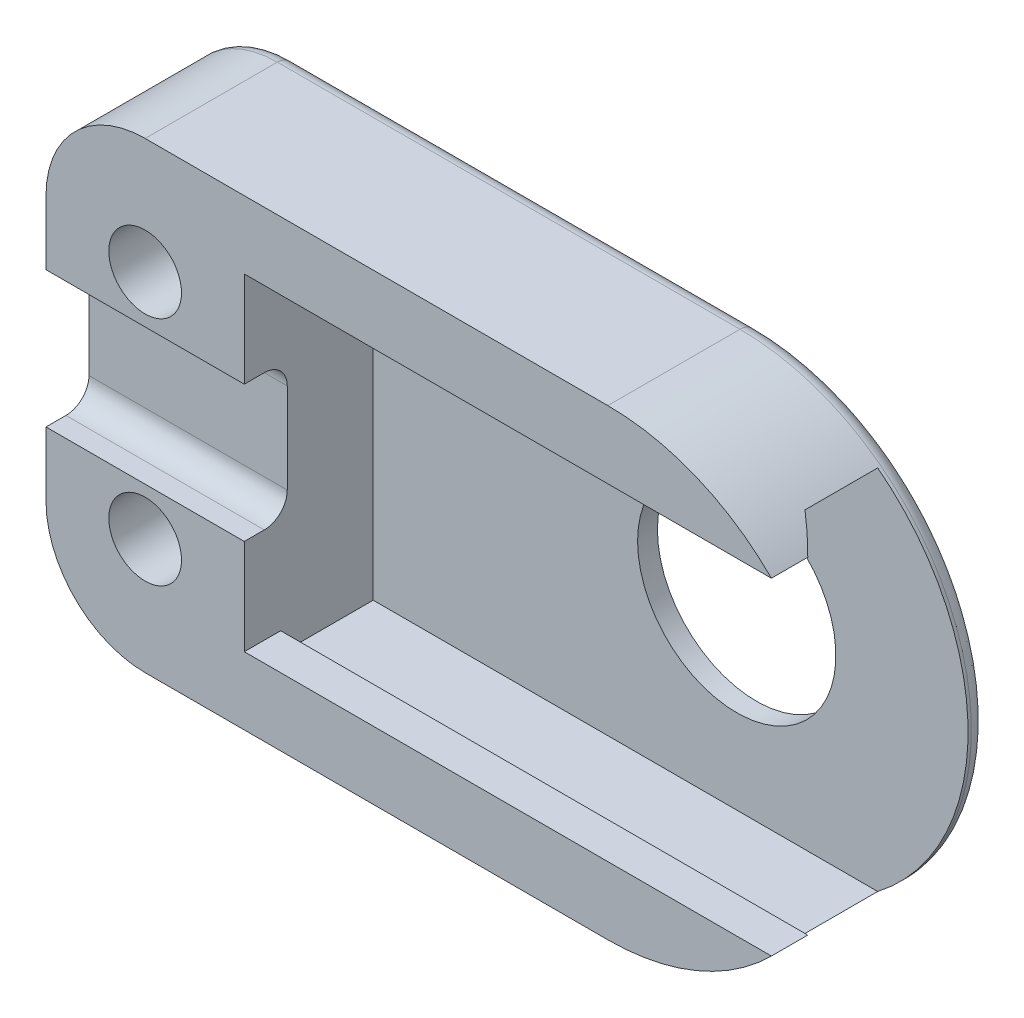
SolidWorks part; units mm, degrees
ref_plane "Front Plane" through (0, 0, 0) normal (0, 0, 1) x (1, 0, 0)
ref_plane "Top Plane" through (0, 0, 0) normal (0, 1, 0) x (1, 0, 0)
ref_plane "Right Plane" through (0, 0, 0) normal (1, 0, 0) x (0, 0, -1)
sketch "Sketch1" plane through (0, 0, 0) normal (0, 0, 1) x (1, 0, 0)
  line L0 (-1.7511, 0) -> (-50001.7511, 0) construction
  line L2 (-17, 7) -> (0, 7)
  line L3 (-17, 7) -> (-17, -7)
  line L4 (-17, -7) -> (0, -7)
  arc A1 (0, 7) -> (0, -7) centre (0, 0) cw
  circle A2 centre (-14, 3.5) radius 1.1
  circle A3 centre (-14, -3.5) radius 1.1
  dimension "D1" = 2.2
  dimension "D2" = 14
  dimension "D3" = 3
  dimension "D4" = 7
  dimension "D5" = 7
extrude "Boss-Extrude1" add sketch "Sketch1" along normal blind 4.5
sketch "Sketch2" plane through (0, 0, 0) normal (0, 0, -1) x (-1, 0, 0)
  circle A0 centre (0, 0) radius 3
  dimension "D1" = 6
extrude "Cut-Extrude2" cut sketch "Sketch2" against normal blind 10
sketch "Sketch7" plane through (-17, 0, 0) normal (-1, 0, 0) x (0, 0, 1)
  line L1 (0.6, 5.55) -> (0.6, -5.55)
  line L2 (0.6, 5.55) -> (2.8, 5.55)
  line L3 (2.8, 5.55) -> (3.4, 4.95)
  line L4 (3.4, 4.95) -> (4.5, 4.95)
  line L5 (4.5, 7) -> (4.5, -7) construction
  line L6 (0, 0) -> (8.4762, 0) construction
  line L7 (0.6, 0) -> (4.5, 0)
  line L8 (4.5, -4.95) -> (4.5, 4.95)
  line L9 (3.4, -4.95) -> (4.5, -4.95)
  line L10 (2.8, -5.55) -> (3.4, -4.95)
  line L11 (0.6, -5.55) -> (2.8, -5.55)
  point P10 (3.95, 4.95)
  line M10 (4.5, -7) -> (4.5, 7)
  dimension "D1" = 45
  dimension "D2" = 2.2
  dimension "D3" = 0.6
  dimension "D4" = 0.6
  dimension "D5" = 11.1
extrude "Cut-Extrude4" cut sketch "Sketch7" against normal through all from offset 6 contours L1 L7 L4 L3 L2 M10 | L1 L11 L10 L9 L7 M10 offset against normal yes
sketch "Sketch8" plane through (-17, 0, 0) normal (-1, 0, 0) x (0, 0, 1)
  line L0 (4.5, 7) -> (4.5, -7) construction
  line L1 (3.2, 1.3633) -> (3.2, -1.3633)
  line L2 (4.5, 2.06) -> (4.5, -2.06)
  line L3 (0, 0) -> (7.1519, 0) construction
  line L4 (4.5, 2.06) -> (3.8967, 2.06)
  line L5 (4.5, -2.06) -> (3.8967, -2.06)
  arc A0 (3.8967, 2.06) -> (3.2, 1.3633) centre (3.8967, 1.3633) ccw
  arc A1 (3.8967, -2.06) -> (3.2, -1.3633) centre (3.8967, -1.3633) cw
  point P8 (3.2, 0)
  point P18 (4.5, 0)
  dimension "D1" = 4.12
  dimension "D2" = 1.3
extrude "Cut-Extrude6" cut sketch "Sketch8" against normal through all
fillet "Fillet4" radius 3 2 edges at (-17, 7, 2.25) (-17, -7, 2.25)
fillet "Fillet1" radius 0.5 6 edges at (-16.1213, 6.1213, 0) (-7, 7, 0) (7, 0, 0) (-7, -7, 0) (-16.1213, -6.1213, 0) (-17, 0, 0)
sketch "Sketch5" plane through (0, 0, 0) normal (0, 0, 1) x (1, 0, 0)
  circle A0 centre (-14, 3.5) radius 1.75
  circle A1 centre (-14, -3.5) radius 1.75
  dimension "D1" = 3.5
extrude "Cut-Extrude5" cut sketch "Sketch5" along normal blind 1
